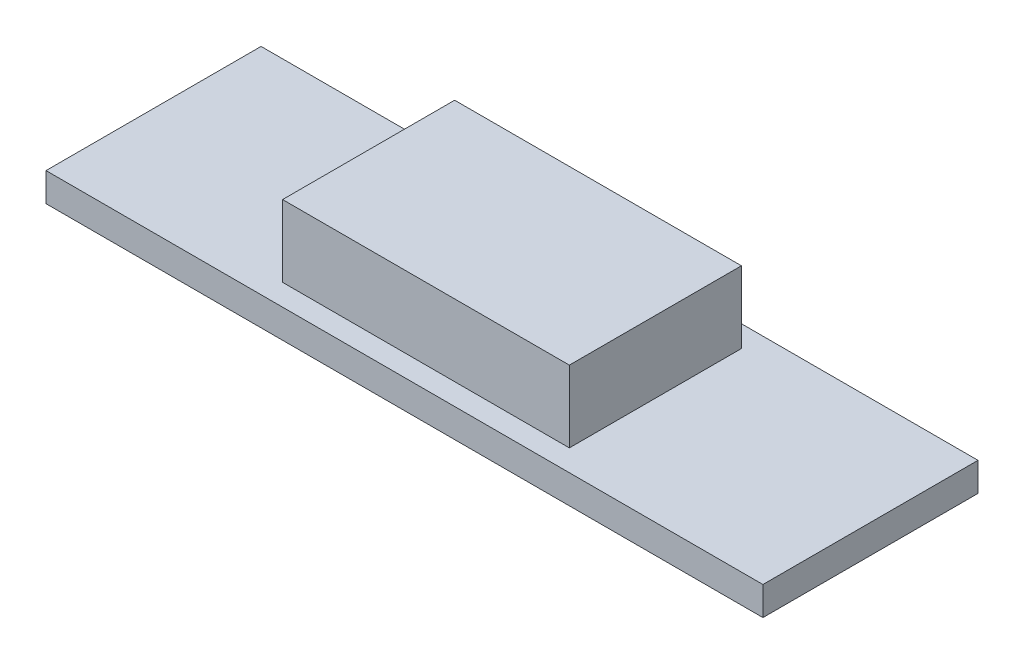
SolidWorks part; units mm, degrees
ref_plane "Front Plane" through (0, 0, 0) normal (0, 0, 1) x (1, 0, 0)
ref_plane "Top Plane" through (0, 0, 0) normal (0, 1, 0) x (1, 0, 0)
ref_plane "Right Plane" through (0, 0, 0) normal (1, 0, 0) x (0, 0, -1)
sketch "Sketch1" plane through (0, 0, 0) normal (0, 1, 0) x (1, 0, 0)
  line L1 (10, -6) -> (-10, -6)
  line L2 (10, -6) -> (10, 6)
  line L3 (10, 6) -> (-10, 6)
  line L4 (-10, -6) -> (-10, 6)
  line L5 (10, -6) -> (-10, 6) construction
  line L6 (10, 6) -> (-10, -6) construction
  point P0 (0, 0)
  dimension "D1" = 20
  dimension "D2" = 12
extrude "Boss-Extrude1" add sketch "Sketch1" along normal blind 5
sketch "Sketch2" plane through (0, 0, 0) normal (0, -1, 0) x (1, 0, 0)
  line L1 (25, -7.5) -> (-25, -7.5)
  line L2 (25, -7.5) -> (25, 7.5)
  line L3 (25, 7.5) -> (-25, 7.5)
  line L4 (-25, -7.5) -> (-25, 7.5)
  line L5 (25, -7.5) -> (-25, 7.5) construction
  line L6 (25, 7.5) -> (-25, -7.5) construction
  point P0 (0, 0)
  dimension "D1" = 50
  dimension "D2" = 15
extrude "Boss-Extrude2" add sketch "Sketch2" along normal blind 2
